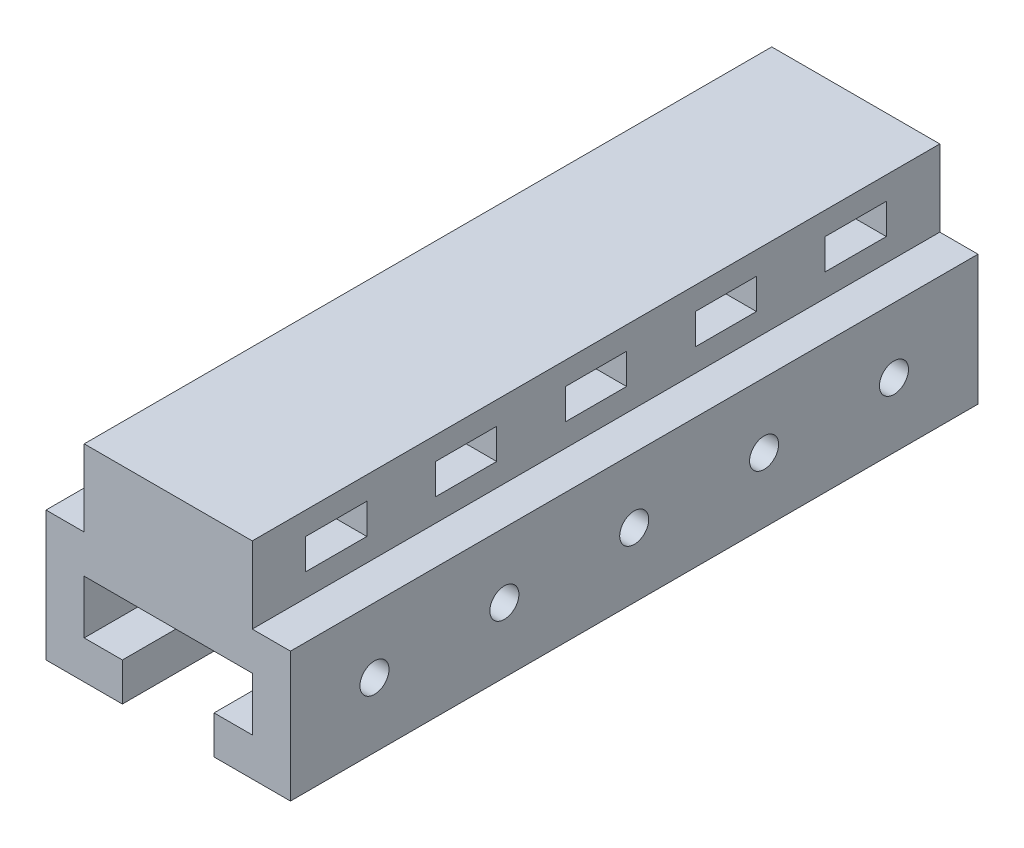
SolidWorks part; units mm, degrees
ref_plane "Спереди" through (0, 0, 0) normal (0, 0, 1) x (1, 0, 0)
ref_plane "Сверху" through (0, 0, 0) normal (0, 1, 0) x (1, 0, 0)
ref_plane "Справа" through (0, 0, 0) normal (1, 0, 0) x (0, 0, -1)
other "Configuration Table"
sketch "Sketch1" plane through (0, 0, 0) normal (0, 0, 1) x (1, 0, 0)
  line L0 (0, 13.4642) -> (0, -26.3494) construction
  line L1 (37.1088, -5) -> (11, -5) construction
  line L3 (11, 5) -> (-11, 5)
  line L4 (11, 5) -> (11, -5)
  line L6 (-11, 5) -> (-11, -5)
  line L7 (11, 5) -> (-11, -5) construction
  line L8 (11, -5) -> (-11, 5) construction
  line L10 (-16, -22) -> (-16, -5)
  line L11 (-16, -5) -> (-11, -5)
  line L12 (16, -22) -> (16, -5)
  line L14 (-11, -17) -> (-6, -17)
  line L15 (-11, -10) -> (11, -10)
  line L16 (-11, -10) -> (-11, -17)
  line L23 (11, -5) -> (16, -5)
  line L24 (-11, -5) -> (-33.4853, -5) construction
  line L25 (-6, -17) -> (-6, -22)
  line L26 (6, -17) -> (6, -22)
  line L27 (11, -17) -> (6, -17)
  line L28 (11, -10) -> (11, -17)
  line L29 (-6, -22) -> (-16, -22)
  line L30 (6, -22) -> (16, -22)
  line L31 (-16, -13.5) -> (16, -13.5) construction
  point P3 (0, 0)
  point P6 (0, 0)
  point P16 (0, -5)
  dimension "D1" = 22
  dimension "D2" = 32
  dimension "D3" = 10
  dimension "D4" = 5
  dimension "D5" = 5
  dimension "D6" = 7
  dimension "D7" = 10
extrude "Boss-Extrude1" add sketch "Sketch1" against normal blind 90
sketch "Sketch2" plane through (16, 0, 0) normal (1, 0, 0) x (0, 0, -1)
  line L0 (0, -13.5) -> (90, -13.5) construction
  line L1 (0, -10) -> (0, -17) construction
  line L2 (90, -22) -> (90, -5) construction
  line L3 (45, -13.5) -> (62, -13.5) construction
  line L4 (45, -13.5) -> (28, -13.5) construction
  circle A0 centre (45, -13.5) radius 1.9
  circle A1 centre (62, -13.5) radius 1.9
  circle A2 centre (79, -13.5) radius 1.9
  circle A3 centre (28, -13.5) radius 1.9
  circle A4 centre (11, -13.5) radius 1.9
  dimension "D1" = 3.8
  dimension "D3" = 17
  dimension "D5" = 17
  dimension "D2" = 3
  dimension "D4" = 3
extrude "Cut-Extrude1" cut sketch "Sketch2" along direction (-1, 0, 0) on the side against the normal through all
sketch "Sketch3" plane through (11, 0, 0) normal (1, 0, 0) x (0, 0, -1)
  line L0 (0, 0) -> (90, 0) construction
  line L1 (0, 5) -> (0, -5) construction
  line L2 (90, -5) -> (90, 5) construction
  line L3 (66, -2) -> (58, -2)
  line L4 (49, 2) -> (41, 2)
  line L5 (49, 2) -> (49, -2)
  line L6 (49, -2) -> (41, -2)
  line L7 (41, 2) -> (41, -2)
  line L8 (49, 2) -> (41, -2) construction
  line L9 (49, -2) -> (41, 2) construction
  line L10 (66, 2) -> (66, -2)
  line L11 (66, 2) -> (58, 2)
  line L12 (58, 2) -> (58, -2)
  line L13 (83, -2) -> (75, -2)
  line L14 (83, 2) -> (83, -2)
  line L15 (83, 2) -> (75, 2)
  line L16 (75, 2) -> (75, -2)
  line L17 (49, -2) -> (66, -2) construction
  line L18 (32, -2) -> (24, -2)
  line L19 (32, 2) -> (32, -2)
  line L20 (32, 2) -> (24, 2)
  line L21 (24, 2) -> (24, -2)
  line L22 (15, -2) -> (7, -2)
  line L23 (15, 2) -> (15, -2)
  line L24 (15, 2) -> (7, 2)
  line L25 (7, 2) -> (7, -2)
  line L26 (49, -2) -> (32, -2) construction
  point P6 (45, 0)
  dimension "D1" = 8
  dimension "D2" = 4
  dimension "D4" = 17
  dimension "D6" = 17
  dimension "D3" = 3
  dimension "D5" = 3
extrude "Cut-Extrude2" cut sketch "Sketch3" against normal through all
